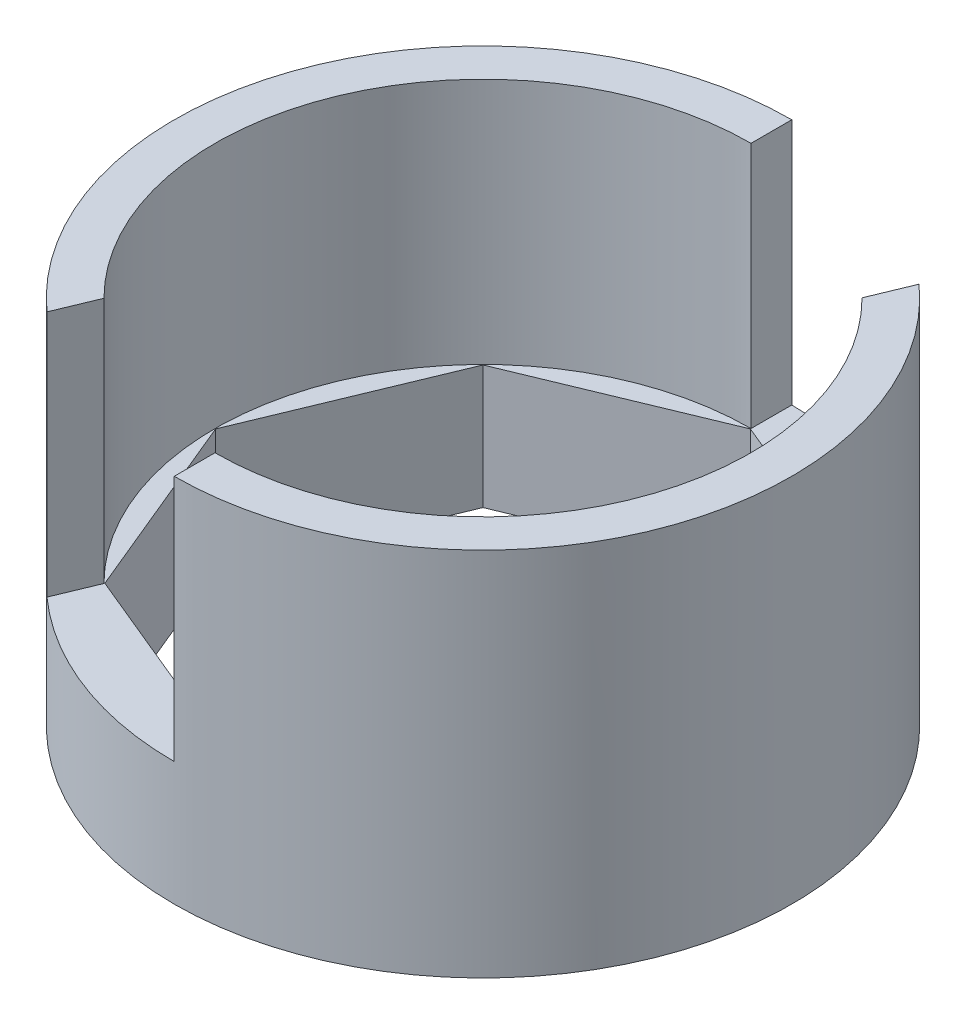
SolidWorks part; units mm, degrees
ref_plane "Front Plane" through (0, 0, 0) normal (0, 0, 1) x (1, 0, 0)
ref_plane "Top Plane" through (0, 0, 0) normal (0, 1, 0) x (1, 0, 0)
ref_plane "Right Plane" through (0, 0, 0) normal (1, 0, 0) x (0, 0, -1)
sketch "Sketch1" plane through (0, 0, 0) normal (0, 1, 0) x (1, 0, 0)
  line L0 (10.8239, 0) -> (7.6537, 7.6537)
  line L1 (0, 10.8239) -> (-7.6537, 7.6537)
  line L2 (-7.6537, 7.6537) -> (-10.8239, 0)
  line L3 (-10.8239, 0) -> (-7.6537, -7.6537)
  line L4 (-7.6537, -7.6537) -> (0, -10.8239)
  line L5 (0, -10.8239) -> (7.6537, -7.6537)
  line L6 (7.6537, -7.6537) -> (10.8239, 0)
  line L7 (7.6537, 7.6537) -> (0, 10.8239)
  circle A0 centre (0, 0) radius 12.5
  circle A1 centre (0, 0) radius 10 construction
  dimension "D1" = 25
  dimension "D2" = 20
extrude "Boss-Extrude1" add sketch "Sketch1" along normal blind 5
sketch "Sketch2" plane through (0, 5, 0) normal (0, 1, 0) x (1, 0, 0)
  line L0 (0, -14.7177) -> (0, 14.1242) construction
  line L2 (7.6537, 7.6537) -> (8.3394, 9.3115)
  line L3 (0, -10.85) -> (-0.6749, -12.4818)
  line L5 (0, 10.8239) -> (0.6864, 12.4811)
  line L6 (-7.6645, -7.6797) -> (-8.3401, -9.3109)
  circle A0 centre (0, 0) radius 12.5
  circle A1 centre (0, 0) radius 10.85
  dimension "D1" = 21.7
extrude "Boss-Extrude3" add sketch "Sketch2" along normal blind 10 contours A1 L0 A0 L6 | L0 A0 L2 A1
